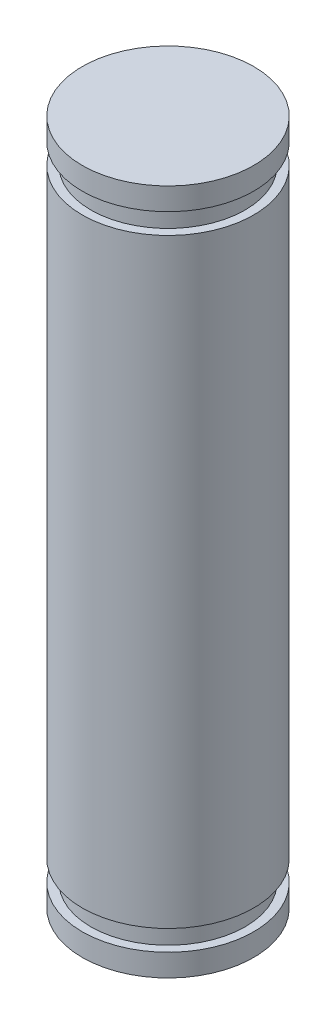
SolidWorks part; units mm, degrees
ref_plane "前视基准面" through (0, 0, 0) normal (0, 0, 1) x (1, 0, 0)
ref_plane "上视基准面" through (0, 0, 0) normal (0, 1, 0) x (1, 0, 0)
ref_plane "右视基准面" through (0, 0, 0) normal (1, 0, 0) x (0, 0, -1)
sketch "草图1" plane through (0, 0, 0) normal (0, 0, 1) x (1, 0, 0)
  line L12 (-6.9556, 36.1149) -> (-11.9556, 36.1149)
  line L13 (-11.9556, 36.1149) -> (-11.9556, 76.1149) construction
  line L14 (-6.9556, 36.1149) -> (-6.9556, 37.4149)
  line L15 (-6.9556, 37.4149) -> (-7.4556, 37.4149)
  line L16 (-7.4556, 37.4149) -> (-7.4556, 38.6149)
  line L17 (-7.4556, 38.6149) -> (-6.9556, 38.6149)
  line L18 (-6.9556, 38.6149) -> (-6.9556, 73.6149)
  line L19 (-6.9556, 73.6149) -> (-7.4556, 73.6149)
  line L20 (-7.4556, 73.6149) -> (-7.4556, 74.8149)
  line L21 (-7.4556, 74.8149) -> (-6.9556, 74.8149)
  line L22 (-6.9556, 74.8149) -> (-6.9556, 76.1149)
  line L23 (-6.9556, 76.1149) -> (-11.9556, 76.1149)
  line L24 (-11.9556, 36.1149) -> (-11.9556, 76.1149)
  dimension "D1" = 40
  dimension "D2" = 35
  dimension "D3" = 5
  dimension "D4" = 1.2
  dimension "D5" = 1.2
  dimension "D6" = 0.5
revolve "旋转1" add sketch "草图1" angle 360 about L13
